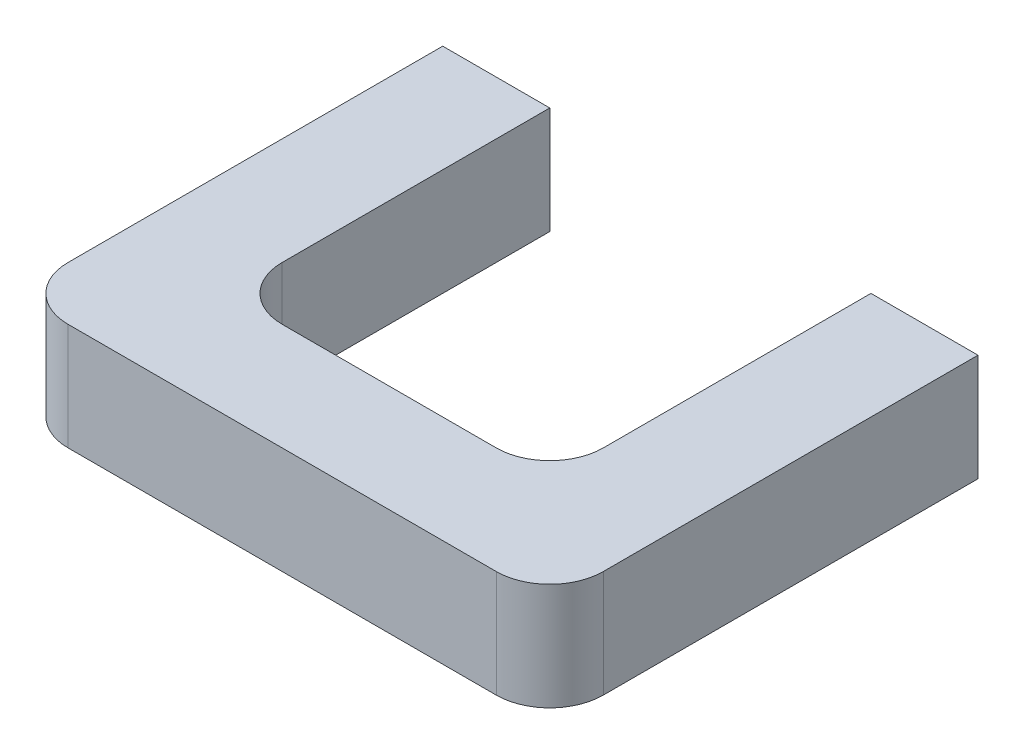
SolidWorks part; units mm, degrees
ref_plane "Front Plane" through (0, 0, 0) normal (0, 0, 1) x (1, 0, 0)
ref_plane "Top Plane" through (0, 0, 0) normal (0, 1, 0) x (1, 0, 0)
ref_plane "Right Plane" through (0, 0, 0) normal (1, 0, 0) x (0, 0, -1)
sketch "Sketch1" plane through (0, 0, 0) normal (0, 1, 0) x (1, 0, 0)
  line L0 (-18.3611, 138.1583) -> (-18.3611, 36.5583)
  line L1 (-18.3611, 36.5583) -> (108.6389, 36.5583)
  line L2 (108.6389, 36.5583) -> (108.6389, 138.1583)
  line L3 (108.6389, 138.1583) -> (83.2389, 138.1583)
  line L4 (83.2389, 138.1583) -> (83.2389, 61.9583)
  line L5 (83.2389, 61.9583) -> (7.0389, 61.9583)
  line L6 (7.0389, 61.9583) -> (7.0389, 138.1583)
  line L7 (7.0389, 138.1583) -> (-18.3611, 138.1583)
  dimension "D1" = 127
  dimension "D2" = 101.6
  dimension "D3" = 76.2
  dimension "D4" = 101.6
  dimension "D5" = 76.2
  dimension "D6" = 25.4
extrude "Boss-Extrude1" add sketch "Sketch1" along normal blind 25.4
fillet "Fillet1" radius 12.7 1 edges at (83.2389, 12.7, -61.9583)
fillet "Fillet2" radius 12.7 1 edges at (7.0389, 12.7, -61.9583)
fillet "Fillet3" radius 12.7 1 edges at (108.6389, 12.7, -36.5583)
fillet "Fillet4" radius 12.7 1 edges at (-18.3611, 12.7, -36.5583)
